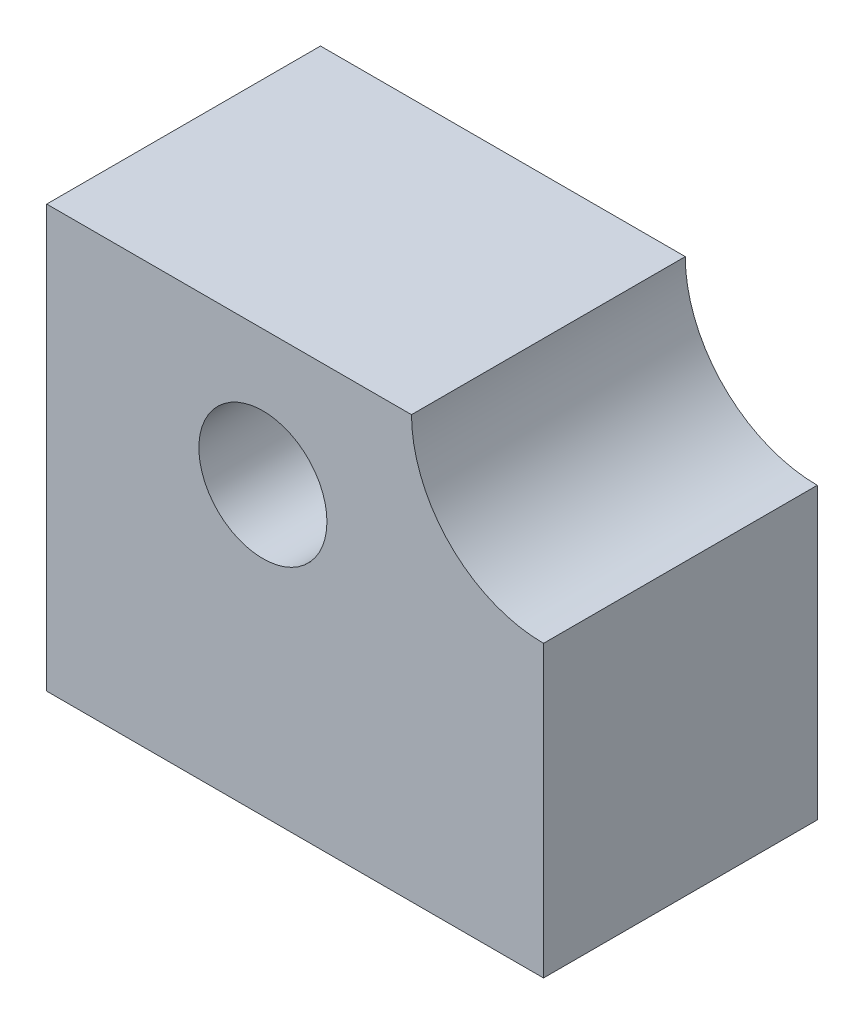
SolidWorks part; units mm, degrees
ref_plane "前视基准面" through (0, 0, 0) normal (0, 0, 1) x (1, 0, 0)
ref_plane "上视基准面" through (0, 0, 0) normal (0, 1, 0) x (1, 0, 0)
ref_plane "右视基准面" through (0, 0, 0) normal (1, 0, 0) x (0, 0, -1)
sketch "草图2" plane through (0, 0, 0) normal (0, 0, 1) x (1, 0, 0)
  line L1 (-31.2879, 30.4119) -> (26.7825, 30.4119)
  line L2 (-31.2879, 30.4119) -> (-31.2879, -18.8979)
  line L3 (-31.2879, -18.8979) -> (26.7825, -18.8979)
  line L4 (26.7825, 30.4119) -> (26.7825, -18.8979)
extrude "凸台-拉伸1" add sketch "草图2" along normal blind 32
sketch "草图3" plane through (0, 0, 32) normal (0, 0, 1) x (1, 0, 0)
  circle A0 centre (-6.018, 14.636) radius 7.484
  circle A1 centre (26.7825, 30.4119) radius 15.4317
extrude "切除-拉伸1" cut sketch "草图3" against normal blind 32
